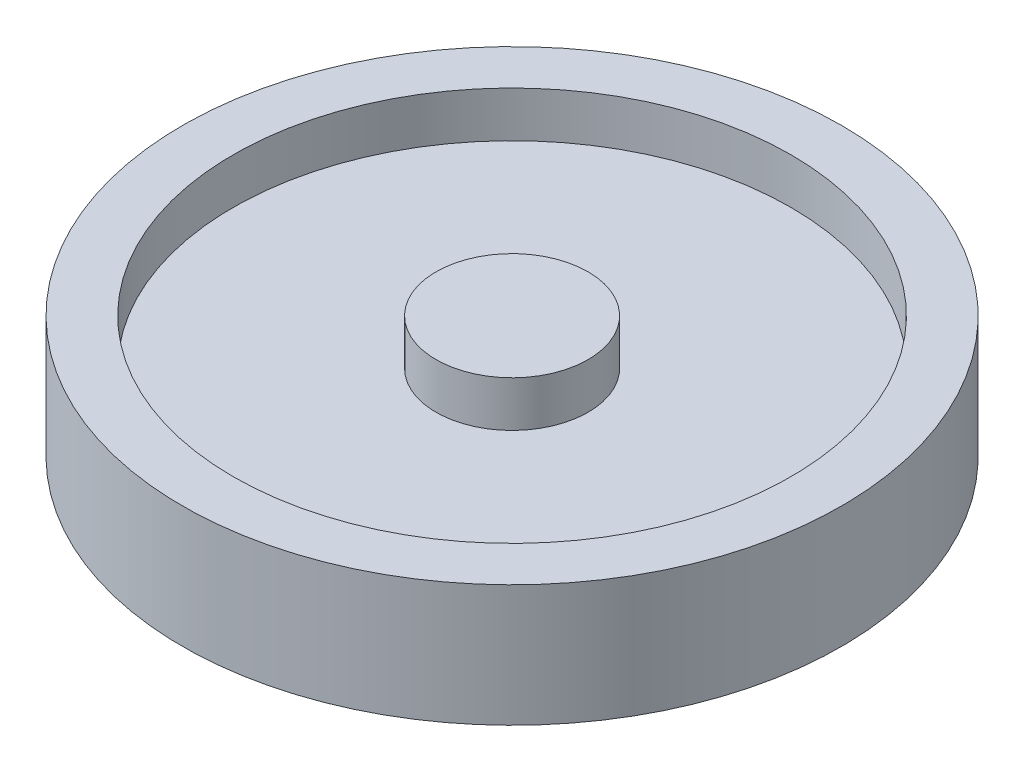
SolidWorks part; units mm, degrees
ref_plane "Front Plane" through (0, 0, 0) normal (1, 0, 0) x (0, 1, 0)
ref_plane "Top Plane" through (0, 0, 0) normal (0, 0, 1) x (0, 1, 0)
ref_plane "Right Plane" through (0, 0, 0) normal (0, 1, 0) x (-1, 0, 0)
sketch "Sketch1" plane through (0, 0, 0) normal (1, 0, 0) x (0, 1, 0)
  line L0 (0, 0) -> (72.8896, 0) construction
  line L1 (55, 0) -> (-55, 0) construction
  line L2 (6, 0) -> (6, 7.5)
  line L3 (6, 7.5) -> (1.5, 7.5)
  line L4 (1.5, 7.5) -> (1.5, 27.5)
  line L5 (1.5, 27.5) -> (6, 27.5)
  line L6 (6, 27.5) -> (6, 32.5)
  line L7 (6, 32.5) -> (-6, 32.5)
  line L8 (-6, 32.5) -> (-6, 27.5)
  line L9 (-6, 27.5) -> (-1.5, 27.5)
  line L10 (-1.5, 27.5) -> (-1.5, 7.5)
  line L11 (-1.5, 7.5) -> (-8, 7.5)
  line L12 (-8, 7.5) -> (-8, 0)
  line L13 (-8, 0) -> (6, 0)
  line L16 (0, -55) -> (0, 55) construction
  line L17 (1.5, 27.5) -> (-1.5, 27.5) construction
  line L18 (0, -32.5) -> (0, 0) construction
  line L19 (0, 0) -> (0, 32.5) construction
  line L20 (27.375, -32.5) -> (-107.375, -32.5) construction
  point P7 (0, 0)
  point P23 (0, -32.5)
  point P25 (0, -32.5)
  point P29 (0, 27.5)
  dimension "D2" = 12
  dimension "D3" = 5
  dimension "D4" = 15
  dimension "D5" = 8
  dimension "D6" = 3
revolve "Revolve1" add sketch "Sketch1" angle 360 about L0
